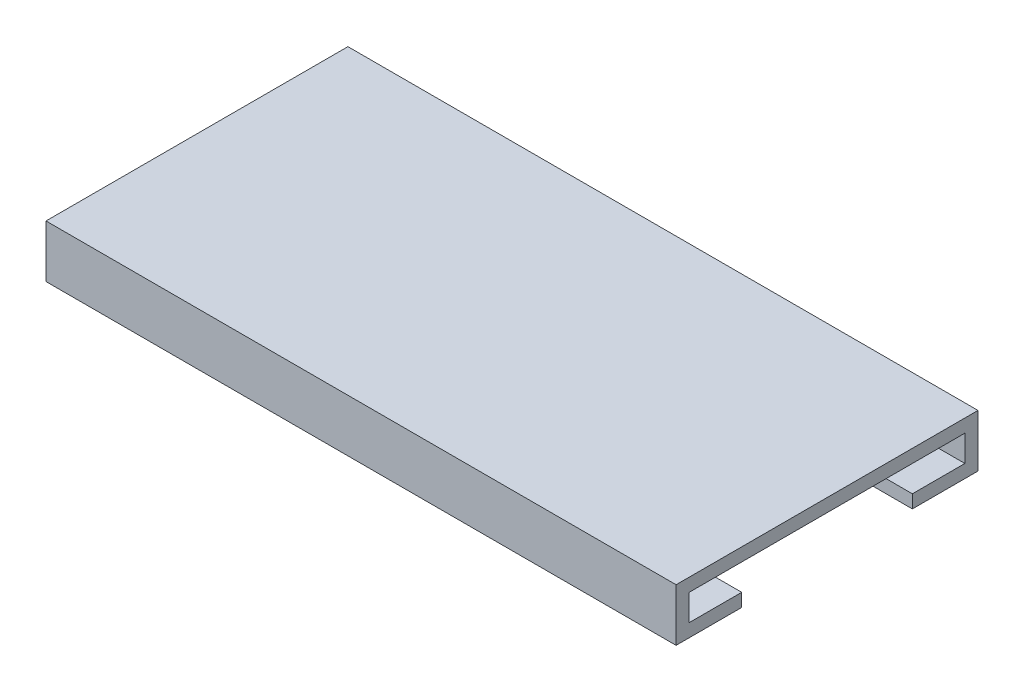
SolidWorks part; units mm, degrees
ref_plane "Front Plane" through (0, 0, 0) normal (0, 0, 1) x (1, 0, 0)
ref_plane "Top Plane" through (0, 0, 0) normal (0, 1, 0) x (1, 0, 0)
ref_plane "Right Plane" through (0, 0, 0) normal (1, 0, 0) x (0, 0, -1)
other "Bounding Box"
ref_plane "Default Plane" through (0, -3.175, 18.2563) normal (0, 0, -1) x (-1, 0, 0)
sketch "Sketch1" plane through (0, 0, 0) normal (1, 0, 0) x (0, 0, -1)
  line L0 (10.3187, -3.175) -> (18.2562, -3.175)
  line L1 (-18.2563, -3.175) -> (-10.3187, -3.175)
  line L2 (-18.2563, -3.175) -> (-18.2563, 3.175)
  line L3 (-18.2563, 3.175) -> (18.2562, 3.175)
  line L4 (18.2562, -3.175) -> (18.2562, 3.175)
  line L5 (-18.2563, -3.175) -> (18.2562, 3.175) construction
  line L6 (-18.2563, 3.175) -> (18.2562, -3.175) construction
  line L11 (-10.3187, -3.175) -> (-10.3187, -1.5875)
  line L13 (10.3187, -3.175) -> (10.3187, -1.5875)
  line L14 (-10.3187, -1.5875) -> (-16.6687, -1.5875)
  line L15 (10.3187, -1.5875) -> (16.6687, -1.5875)
  line L16 (-16.6687, -1.5875) -> (-16.6687, 1.5875)
  line L17 (16.6687, -1.5875) -> (16.6687, 1.5875)
  line L18 (-16.6687, 1.5875) -> (16.6687, 1.5875)
  point P0 (0, 0)
  dimension "D1" = 36.5125
  dimension "D2" = 6.35
  dimension "D5" = 1.5875
  dimension "D6" = 1.5875
  dimension "D7" = 6.35
  dimension "D8" = 6.35
  dimension "D9" = 3.175
  dimension "D10" = 3.175
extrude "Boss-Extrude1" add sketch "Sketch1" along normal blind 76.2
